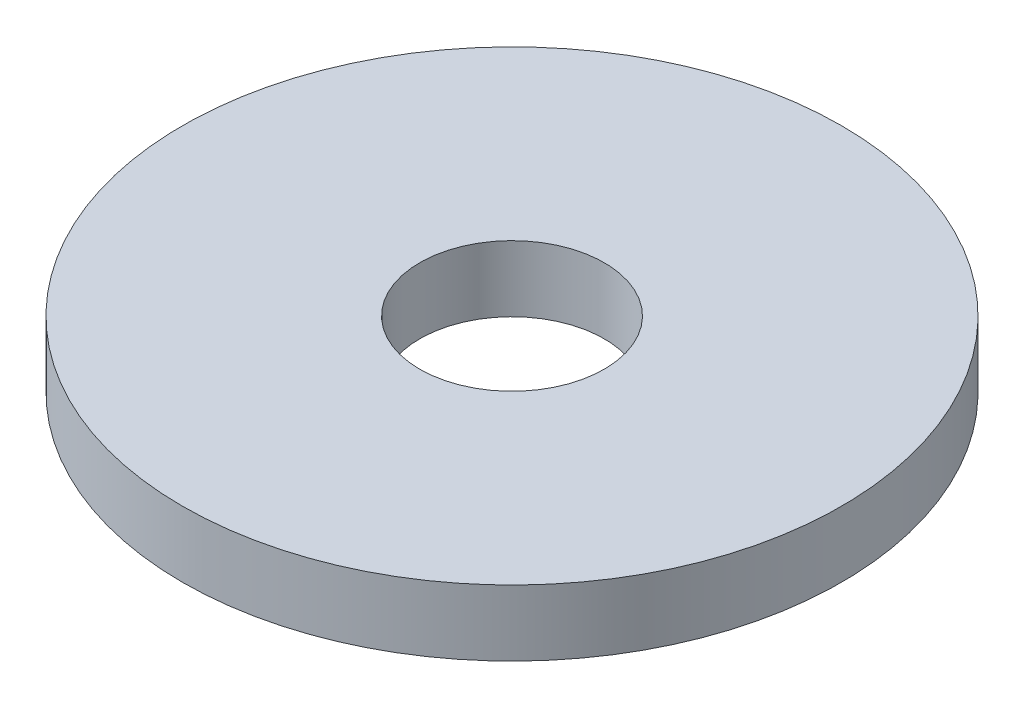
SolidWorks part; units mm, degrees
material "AISI 304"
ref_plane "Спереди" through (0, 0, 0) normal (0, 0, 1) x (1, 0, 0)
ref_plane "Сверху" through (0, 0, 0) normal (0, 1, 0) x (1, 0, 0)
ref_plane "Справа" through (0, 0, 0) normal (1, 0, 0) x (0, 0, -1)
sketch "Эскиз1" plane through (0, 0, 0) normal (0, 1, 0) x (1, 0, 0)
  circle A0 centre (0, 0) radius 25
  circle A1 centre (0, 0) radius 7
  dimension "D1" = 50
  dimension "D2" = 14
extrude "Бобышка-Вытянуть1" add sketch "Эскиз1" along normal blind 5
